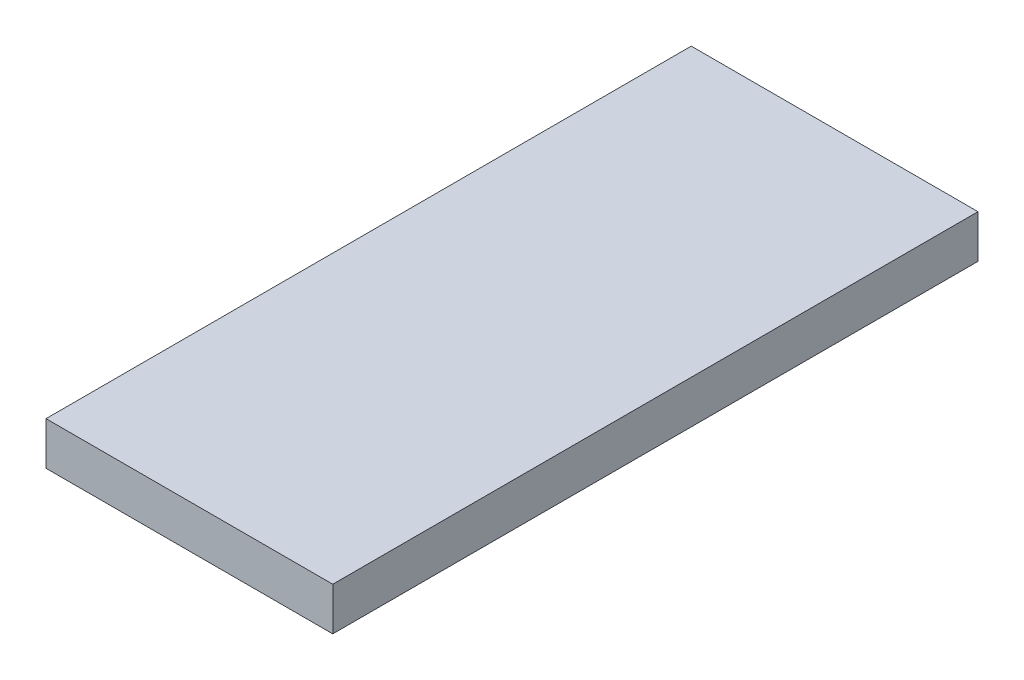
SolidWorks part; units mm, degrees
ref_plane "Front Plane" through (0, 0, 0) normal (0, 0, 1) x (1, 0, 0)
ref_plane "Top Plane" through (0, 0, 0) normal (0, 1, 0) x (1, 0, 0)
ref_plane "Right Plane" through (0, 0, 0) normal (1, 0, 0) x (0, 0, -1)
sketch "Sketch1" plane through (0, 0, 0) normal (0, 1, 0) x (1, 0, 0)
  line L1 (0, 0) -> (40, 0)
  line L2 (0, 0) -> (0, 90)
  line L3 (0, 90) -> (40, 90)
  line L4 (40, 0) -> (40, 90)
extrude "Boss-Extrude1" add sketch "Sketch1" along normal blind 6
